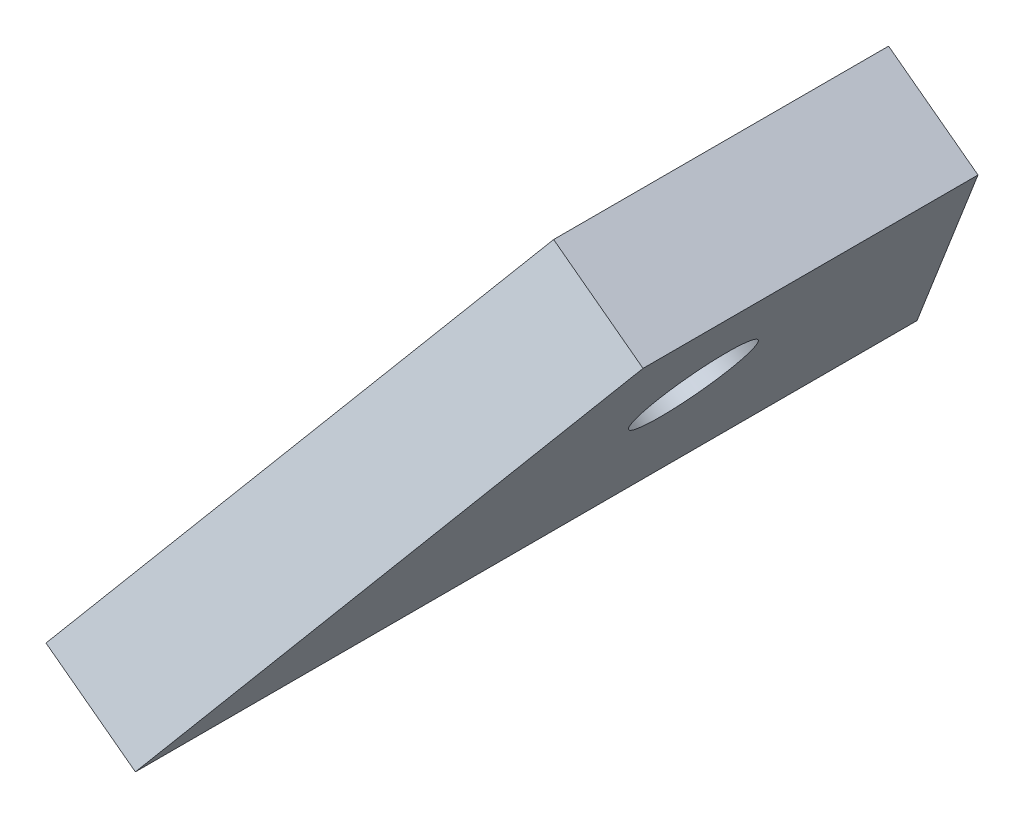
SolidWorks part; units mm, degrees
material "6061-T6 (SS)"
ref_plane "Alzado" through (0, 0, 0) normal (0, 0, 1) x (1, 0, 0)
ref_plane "Planta" through (0, 0, 0) normal (0, 1, 0) x (1, 0, 0)
ref_plane "Vista lateral" through (0, 0, 0) normal (1, 0, 0) x (0, 0, -1)
sketch3d "Sk_Plano_Yugo"
  point P0 (-234.5664, 351.3361, 0)
  point P1 (-234.5664, 351.3361, 10)
  point P2 (-228.5751, 359.3426, 0)
ref_plane "Plano_Yugo" through (-318.9017, 238.633, 0) normal (-0.8007, 0.5991, 0) x (0, 0, 1)
sketch "Sk_Yugo" plane through (-318.9017, 238.633, 0) normal (-0.8007, 0.5991, 0) x (0, 0, 1)
  line L0 (-14, 203.7638) -> (14, 203.7638)
  line L1 (14, 203.7638) -> (6, 220.7638)
  line L2 (6, 220.7638) -> (-6, 220.7638)
  line L3 (-6, 220.7638) -> (-14, 203.7638)
extrude "Yugo" add sketch "Sk_Yugo" along normal blind 4
sketch3d "Sk_Ojo_cable"
  line L0 (-190.0295, 409.1847, 0) -> (-194.8334, 412.7795, 0)
  dimension "D1" = 6
sweep "Ojo_cable" cut path "Sk_Ojo_cable" circular profile diameter 4 parameters "D3"=4
